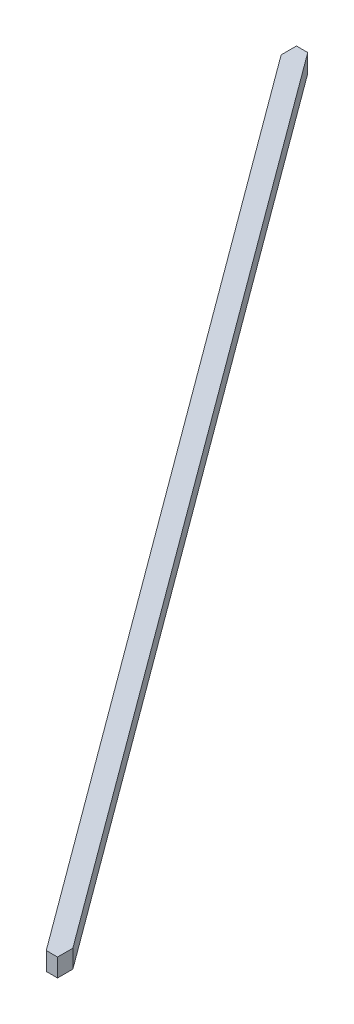
SolidWorks part; units mm, degrees
ref_plane "Front Plane" through (0, 0, 0) normal (0, 0, 1) x (1, 0, 0)
ref_plane "Top Plane" through (0, 0, 0) normal (0, 1, 0) x (1, 0, 0)
ref_plane "Right Plane" through (0, 0, 0) normal (1, 0, 0) x (0, 0, -1)
sketch "Sketch3" plane through (0, 0, 0) normal (0, 1, 0) x (1, 0, 0)
  line L0 (0, 0) -> (0, 1000) construction
  line L1 (0, 1000) -> (737, 1000) construction
  line L2 (737, 1000) -> (737, 0) construction
  line L3 (737, 0) -> (0, 0) construction
  line L4 (0, 1000) -> (737, 0) construction
  line L5 (0, 1000) -> (12.4224, 1000)
  line L6 (12.4224, 1000) -> (737, 16.8554)
  line L7 (737, 16.8554) -> (737, 0)
  line L8 (737, 0) -> (724.5776, 0)
  line L9 (724.5776, 0) -> (0, 983.1446)
  line L10 (0, 983.1446) -> (0, 1000)
  dimension "D1" = 1000
  dimension "D2" = 737
  dimension "D3" = 10
  dimension "D4" = 20
extrude "Boss-Extrude2" add sketch "Sketch3" along normal blind 20 contours L10 L5 L6 L7 L8 L9
